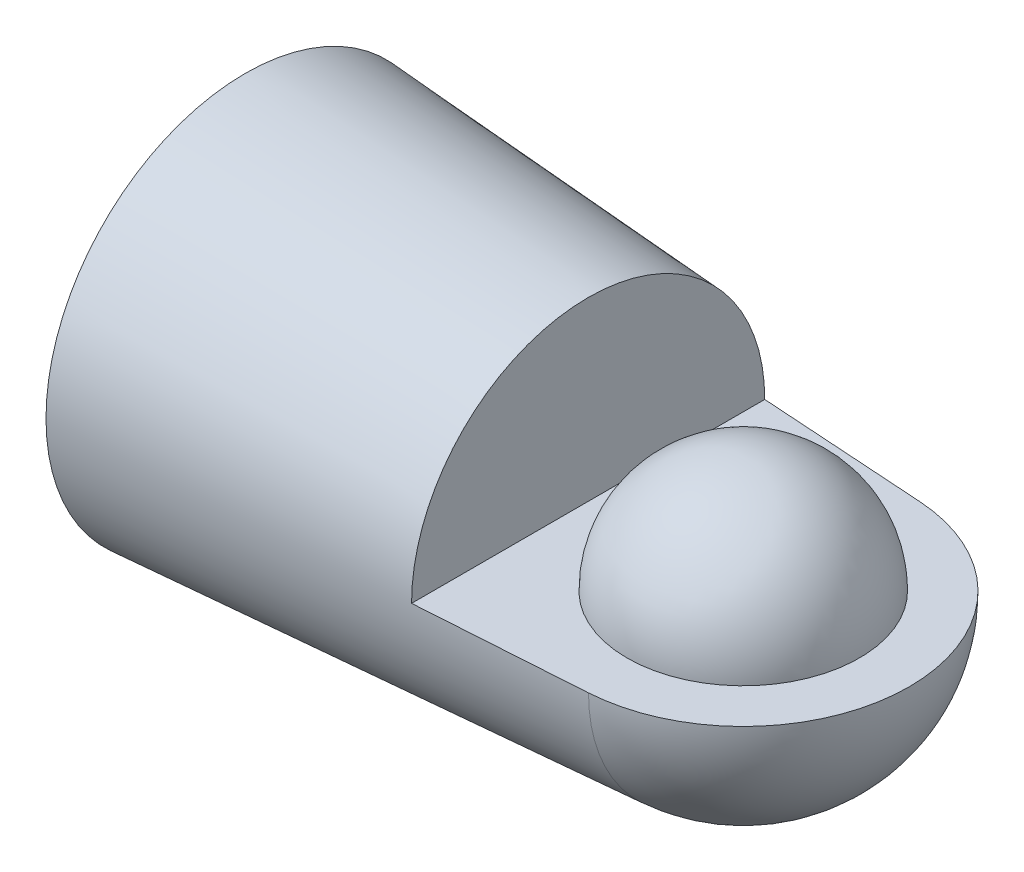
SolidWorks part; units mm, degrees
ref_plane "Front Plane" through (0, 0, 0) normal (0, 0, 1) x (1, 0, 0)
ref_plane "Top Plane" through (0, 0, 0) normal (0, 1, 0) x (1, 0, 0)
ref_plane "Right Plane" through (0, 0, 0) normal (1, 0, 0) x (0, 0, -1)
sketch "Sketch1" plane through (0, 0, 0) normal (0, 1, 0) x (1, 0, 0)
  line L0 (0, 0) -> (-150, 0)
  line L1 (-150, 0) -> (-150, 60)
  line L3 (-150, 60) -> (3.29, 49.8916)
  line L4 (0, 0) -> (50, 0)
  arc A0 (50, 0) -> (3.29, 49.8916) centre (0, 0) ccw
  dimension "D1" = 100
  dimension "D2" = 150
  dimension "D3" = 60
revolve "Revolve1" add sketch "Sketch1" angle 360 about L0
sketch "Sketch2" plane through (0, 0, 0) normal (0, 1, 0) x (1, 0, 0)
  line L0 (3.29, 49.8916) -> (3.29, -49.8916) construction
  line L1 (-46.71, -60) -> (53.29, -60)
  line L2 (-46.71, -60) -> (-46.71, 60)
  line L3 (-46.71, 60) -> (53.29, 60)
  line L4 (53.29, -60) -> (53.29, 60)
  line L5 (-46.71, -60) -> (53.29, 60) construction
  line L6 (-46.71, 60) -> (53.29, -60) construction
  point P0 (3.29, 0)
  dimension "D1" = 100
  dimension "D2" = 120
extrude "Cut-Extrude1" cut sketch "Sketch2" along normal blind 82
sketch "Sketch3" plane through (0, 0, 0) normal (0, 1, 0) x (1, 0, 0)
  line L0 (-35, 0) -> (35, 0)
  arc A0 (35, 0) -> (-35, 0) centre (0, 0) ccw
  dimension "D1" = 70
revolve "Revolve2" add sketch "Sketch3" angle 360 about L0
sketch "Sketch4" plane through (-150, 0, 0) normal (-1, 0, 0) x (0, 0, 1)
  circle A0 centre (0, 0) radius 50
  dimension "D1" = 100
extrude "Cut-Extrude2" cut sketch "Sketch4" against normal blind 20
